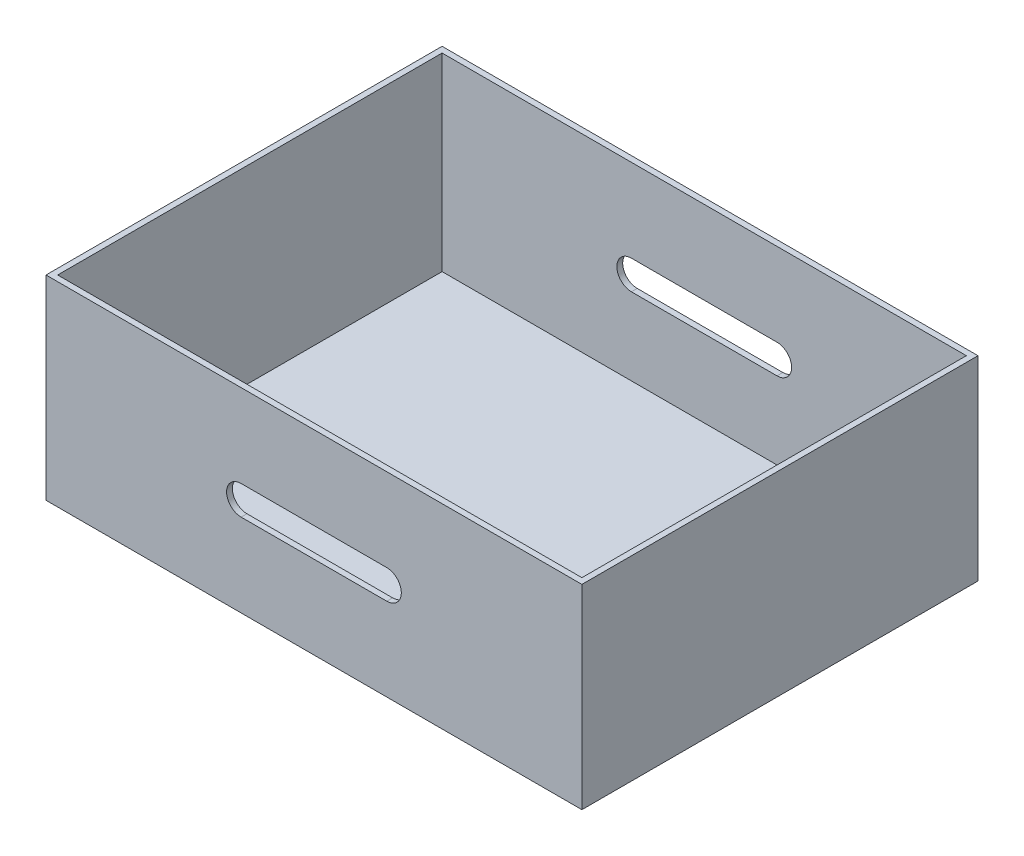
SolidWorks part; units mm, degrees
ref_plane "Plano frontal" through (0, 0, 0) normal (0, 0, 1) x (1, 0, 0)
ref_plane "Plano superior" through (0, 0, 0) normal (0, 1, 0) x (1, 0, 0)
ref_plane "Plano direito" through (0, 0, 0) normal (1, 0, 0) x (0, 0, -1)
sketch "Esboço1" plane through (0, 0, 0) normal (0, 1, 0) x (1, 0, 0)
  line L5 (-92, -68) -> (92, -68)
  line L6 (-92, -68) -> (-92, 68)
  line L7 (-92, 68) -> (92, 68)
  line L8 (92, -68) -> (92, 68)
  line L13 (-92, -68) -> (92, 68) construction
  line L14 (-92, 68) -> (92, -68) construction
  point P0 (0, 0)
  dimension "D1" = 184
  dimension "D2" = 136
extrude "Ressalto-extrusão1" add sketch "Esboço1" along normal blind 2
sketch "Esboço2" plane through (0, 2, 0) normal (0, 1, 0) x (1, 0, 0)
  line L1 (-90, -66) -> (90, -66)
  line L2 (-90, -66) -> (-90, 66)
  line L3 (-90, 66) -> (90, 66)
  line L4 (90, -66) -> (90, 66)
  line L5 (-90, -66) -> (90, 66) construction
  line L6 (-90, 66) -> (90, -66) construction
  point P0 (0, 0)
  dimension "D1" = 180
  dimension "D2" = 132
extrude "Extrusão-Fina1" add sketch "Esboço2" along normal blind 65 thin
sketch "Esboço3" plane through (0, 0, 68) normal (0, 0, 1) x (1, 0, 0)
  line L0 (0, 0) -> (0, 67) construction
  line L1 (-92, 0) -> (92, 0) construction
  line L2 (-92, 67) -> (92, 67) construction
  line L3 (92, 33.5) -> (-92, 33.5) construction
  line L4 (92, 67) -> (92, 0) construction
  line L5 (-92, 67) -> (-92, 0) construction
  line L6 (-25, 33.5) -> (25, 33.5) construction
  line L7 (-25, 38.5) -> (25, 38.5)
  line L8 (-25, 28.5) -> (25, 28.5)
  arc A0 (-25, 38.5) -> (-25, 28.5) centre (-25, 33.5) ccw
  arc A1 (25, 28.5) -> (25, 38.5) centre (25, 33.5) ccw
  point P14 (0, 33.5)
  dimension "D1" = 50
  dimension "D2" = 10
extrude "Corte-extrusão1" cut sketch "Esboço3" against normal through all
